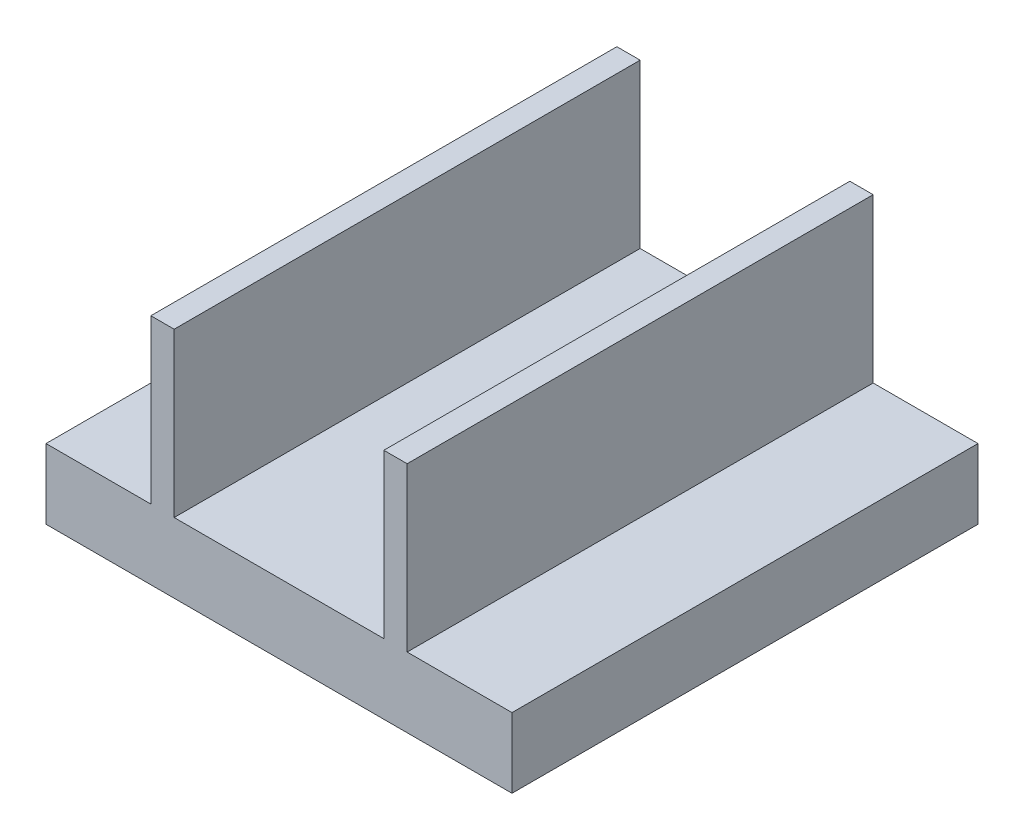
SolidWorks part; units mm, degrees
ref_plane "Спереди" through (0, 0, 0) normal (0, 0, 1) x (1, 0, 0)
ref_plane "Сверху" through (0, 0, 0) normal (0, 1, 0) x (1, 0, 0)
ref_plane "Справа" through (0, 0, 0) normal (1, 0, 0) x (0, 0, -1)
sketch "Эскиз1" plane through (0, 0, 0) normal (0, 0, 1) x (1, 0, 0)
  line L0 (0, 0) -> (20, 0)
  line L1 (20, 0) -> (20, 3)
  line L2 (0, 0) -> (0, 3)
  line L3 (0, 3) -> (4.5, 3)
  line L4 (20, 3) -> (15.5, 3)
  line L5 (4.5, 3) -> (4.5, 10)
  line L6 (15.5, 3) -> (15.5, 10)
  line L7 (4.5, 10) -> (5.5, 10)
  line L8 (15.5, 10) -> (14.5, 10)
  line L9 (5.5, 10) -> (5.5, 3)
  line L10 (14.5, 10) -> (14.5, 3)
  line L12 (5.5, 3) -> (14.5, 3)
extrude "Бобышка-Вытянуть1" add sketch "Эскиз1" along normal blind 20
